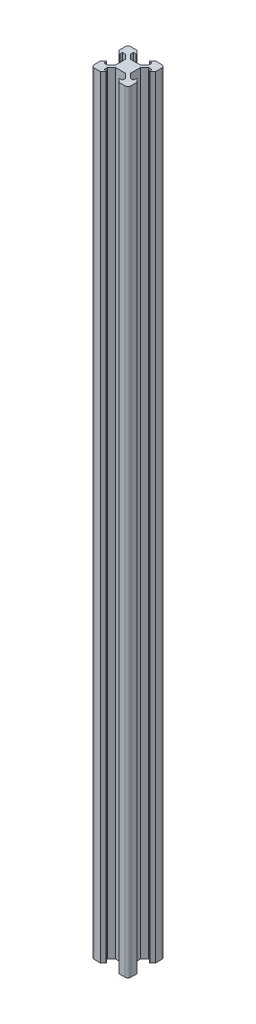
SolidWorks part; units mm, degrees
ref_plane "Спереди" through (0, 0, 0) normal (0, 0, 1) x (1, 0, 0)
ref_plane "Сверху" through (0, 0, 0) normal (0, 1, 0) x (1, 0, 0)
ref_plane "Справа" through (0, 0, 0) normal (1, 0, 0) x (0, 0, -1)
sketch "Эскиз1" plane through (0, 0, 0) normal (0, 1, 0) x (1, 0, 0)
  line L0 (8, 5) -> (6.2728, 5)
  line L1 (8.5, 10) -> (-8.5, 10)
  line L2 (10, 8.5) -> (10, -8.5)
  line L3 (8.5, -10) -> (-8.5, -10)
  line L4 (-10, 8.5) -> (-10, -8.5)
  line L5 (10, 10) -> (-10, -10) construction
  line L6 (10, -10) -> (-10, 10) construction
  line L7 (5, -10) -> (3.5121, -8.5121)
  line L8 (8, 5) -> (5, 5)
  line L9 (8, 5) -> (8, 3.7243)
  line L10 (8, -5) -> (6.2728, -5)
  line L11 (10, 5) -> (8.5121, 3.5121)
  line L12 (8, -5) -> (8, -3.7243)
  line L13 (10, 0) -> (-10, 0) construction
  line L14 (10, -5) -> (8.5121, -3.5121)
  line L15 (5, -8) -> (3.7243, -8)
  line L16 (5, -8) -> (5, -6.2728)
  line L17 (5, -6.2728) -> (2.7272, -4)
  line L18 (2.7272, -4) -> (-2.7272, -4)
  line L19 (-2.7272, -4) -> (-5, -6.2728)
  line L20 (-5, -8) -> (-5, -6.2728)
  line L21 (-5, -8) -> (-3.7243, -8)
  line L22 (-5, -10) -> (-3.5121, -8.5121)
  line L23 (-10, -5) -> (-8.5121, -3.5121)
  line L24 (-8, -5) -> (-8, -3.7243)
  line L25 (-8, -5) -> (-6.2728, -5)
  line L26 (-6.2728, -5) -> (-4, -2.7272)
  line L27 (-4, -2.7272) -> (-4, 2.7272)
  line L28 (-4, 2.7272) -> (-6.2728, 5)
  line L29 (-8, 5) -> (-6.2728, 5)
  line L30 (-8, 5) -> (-8, 3.7243)
  line L31 (-10, 5) -> (-8.5121, 3.5121)
  line L32 (-5, 10) -> (-3.5121, 8.5121)
  line L33 (-5, 8) -> (-3.7243, 8)
  line L34 (-5, 8) -> (-5, 6.2728)
  line L35 (-5, 6.2728) -> (-2.7272, 4)
  line L36 (6.2728, 5) -> (4, 2.7272)
  line L37 (-2.7272, 4) -> (2.7272, 4)
  line L38 (4, -2.7272) -> (6.2728, -5)
  line L39 (2.7272, 4) -> (5, 6.2728)
  line L40 (4, 2.7272) -> (4, -2.7272)
  line L41 (5, 8) -> (5, 6.2728)
  line L42 (5, 10) -> (5, 4) [skipped]
  line L43 (5, 8) -> (3, 8) [skipped]
  line L44 (5, 10) -> (3, 8) [skipped]
  line L45 (5, -10) -> (5, -4) [skipped]
  line L46 (5, -10) -> (3, -8) [skipped]
  line L47 (5, -8) -> (3, -8) [skipped]
  line L48 (-5, -10) -> (-5, -4) [skipped]
  line L49 (-5, -8) -> (-3, -8) [skipped]
  line L50 (-5, -10) -> (-3, -8) [skipped]
  line L51 (-10, -5) -> (-4, -5) [skipped]
  line L52 (-8, 5) -> (-8, 3) [skipped]
  line L53 (-10, 5) -> (-4, 5) [skipped]
  line L54 (-5, 10) -> (-5, 4) [skipped]
  line L55 (-5, 8) -> (-3, 8) [skipped]
  line L56 (-5, 10) -> (-3, 8) [skipped]
  line L57 (-10, 5) -> (-8, 3) [skipped]
  line L58 (-8, -5) -> (-8, -3) [skipped]
  line L59 (-10, -5) -> (-8, -3) [skipped]
  line L60 (5, 8) -> (3.7243, 8)
  line L61 (5, 10) -> (3.5121, 8.5121)
  arc A0 (-8.5, -10) -> (-10, -8.5) centre (-8.5, -8.5) cw
  arc A1 (-8.5, 10) -> (-10, 8.5) centre (-8.5, 8.5) ccw
  arc A2 (10, -8.5) -> (8.5, -10) centre (8.5, -8.5) cw
  arc A3 (8.5, 10) -> (10, 8.5) centre (8.5, 8.5) cw
  arc A4 (8, 3.7243) -> (8.5121, 3.5121) centre (8.3, 3.7243) ccw
  arc A5 (8, -3.7243) -> (8.5121, -3.5121) centre (8.3, -3.7243) cw
  arc A6 (-8, 3.7243) -> (-8.5121, 3.5121) centre (-8.3, 3.7243) cw
  arc A7 (-8.5121, -3.5121) -> (-8, -3.7243) centre (-8.3, -3.7243) cw
  arc A8 (-3.7243, -8) -> (-3.5121, -8.5121) centre (-3.7243, -8.3) cw
  arc A9 (3.5121, -8.5121) -> (3.7243, -8) centre (3.7243, -8.3) cw
  arc A10 (3.7243, 8) -> (3.5121, 8.5121) centre (3.7243, 8.3) cw
  arc A11 (-3.7243, 8) -> (-3.5121, 8.5121) centre (-3.7243, 8.3) ccw
  point P0 (0, 0)
  point P12 (4, 0)
  point P20 (0, 0)
  point P21 (0, 0)
  point P29 (0, 0)
  point P33 (0, 0)
  point P38 (0, 0)
  point P45 (0, 0)
  point P47 (0, 0)
  point P96 (0, 0)
  point P108 (8, 3)
  point P111 (8, -3)
  dimension "D13" = 1.5
  dimension "D14" = 0.3
  dimension "D1" = 3
  dimension "D2" = 2
  dimension "D3" = 5
  dimension "D4" = 6
  dimension "D5" = 20
  dimension "D6" = 20
  dimension "D8" = 0.9
  dimension "D9" = 0.9
  dimension "D10" = 3.7272
  dimension "D11" = 5
  dimension "D7" = 4
  dimension "D12" = 4
extrude "Бобышка-Вытянуть1" add sketch "Эскиз1" along normal blind 420
